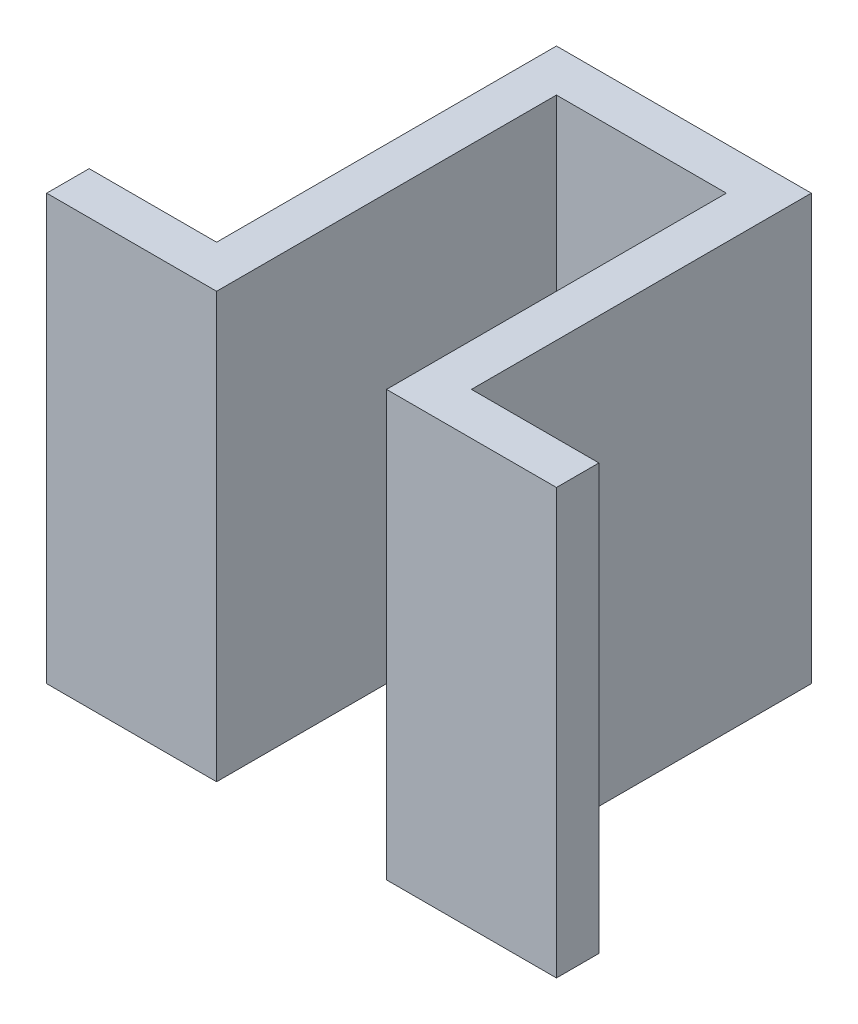
SolidWorks part; units mm, degrees
material "AISI 1015 Steel, Cold Drawn (SS)"
ref_plane "Front Plane" through (0, 0, 0) normal (0, 0, 1) x (1, 0, 0)
ref_plane "Top Plane" through (0, 0, 0) normal (0, 1, 0) x (1, 0, 0)
ref_plane "Right Plane" through (0, 0, 0) normal (1, 0, 0) x (0, 0, -1)
sketch "Sketch1" plane through (0, 0, 0) normal (0, 1, 0) x (1, 0, 0)
  line L0 (76.2, -88.9) -> (76.2, -101.6)
  line L1 (76.2, -101.6) -> (25.4, -101.6)
  line L2 (25.4, -101.6) -> (25.4, 0)
  line L3 (25.4, 0) -> (-25.4, 0)
  line L4 (-25.4, 0) -> (-25.4, -101.6)
  line L5 (-25.4, -101.6) -> (-76.2, -101.6)
  line L6 (-76.2, -101.6) -> (-76.2, -88.9)
  line L7 (-76.2, -88.9) -> (-38.1, -88.9)
  line L8 (-38.1, -88.9) -> (-38.1, 12.7)
  line L9 (-38.1, 12.7) -> (38.1, 12.7)
  line L10 (38.1, 12.7) -> (38.1, -88.9)
  line L11 (38.1, -88.9) -> (76.2, -88.9)
  line L12 (38.1, -2.4592) -> (25.4, -2.4592) construction
  line L13 (0, 0) -> (0, 12.7) construction
  line L14 (-25.4, -37.1255) -> (-38.1, -37.1255) construction
  dimension "D1" = 101.6
  dimension "D2" = 50.8
  dimension "D3" = 12.7
  dimension "D4" = 12.7
  dimension "D5" = 50.8
extrude "Boss-Extrude1" add sketch "Sketch1" along normal blind 127
